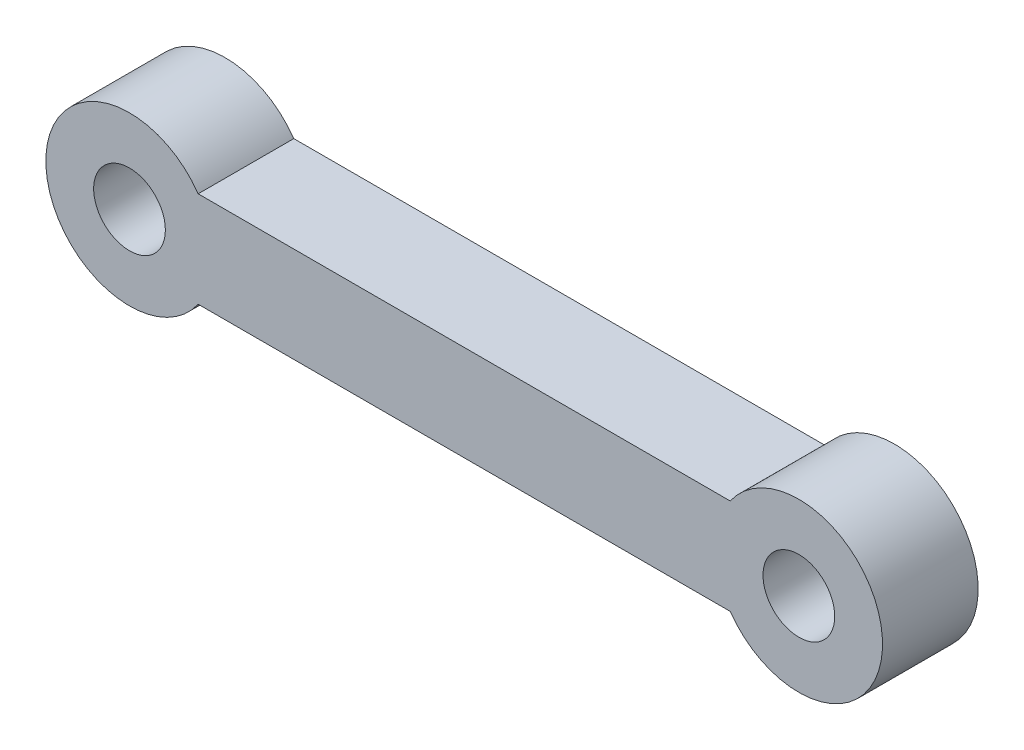
SolidWorks part; units mm, degrees
ref_plane "Front Plane" through (0, 0, 0) normal (0, 0, 1) x (1, 0, 0)
ref_plane "Top Plane" through (0, 0, 0) normal (0, 1, 0) x (1, 0, 0)
ref_plane "Right Plane" through (0, 0, 0) normal (1, 0, 0) x (0, 0, -1)
sketch "Sketch1" plane through (0, 0, 0) normal (0, 0, 1) x (1, 0, 0)
  line L0 (120, 10) -> (130, 10) construction
  line L1 (0, 0) -> (120, 0)
  line L2 (0, 0) -> (0, 20)
  line L3 (0, 20) -> (120, 20)
  line L4 (120, 0) -> (120, 20)
  line L5 (0, 10) -> (-10, 10) construction
  circle A0 centre (130, 10) radius 7.5
  circle A1 centre (130, 10) radius 17.5
  circle A2 centre (-10, 10) radius 7.5
  circle A3 centre (-10, 10) radius 17.5
  dimension "D3" = 10
  dimension "D4" = 15
  dimension "D5" = 35
  dimension "D7" = 15
  dimension "D8" = 35
  dimension "D1" = 120
  dimension "D2" = 20
  dimension "D6" = 10
extrude "Boss-Extrude2" add sketch "Sketch1" along normal blind 20 contours A3 L1 A1 L3 | L1 A3 L3 L2 | L3 A1 L1 L4 | L1 A1 L3 L4 A0 | L3 A3 L1 L2 A2
